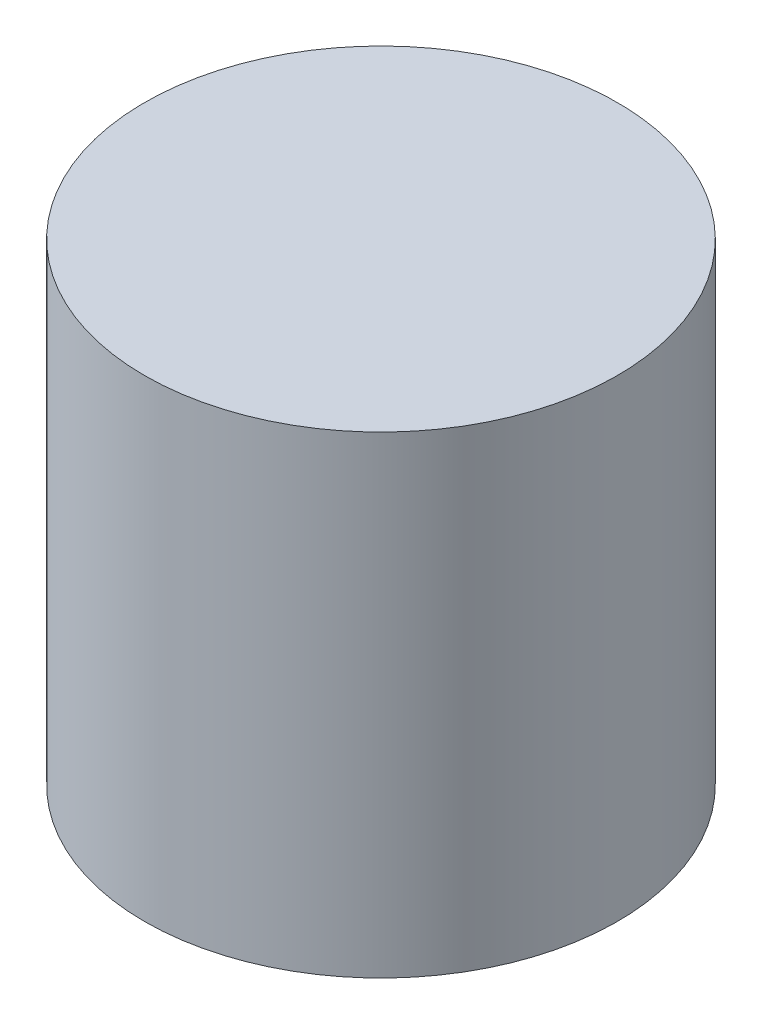
SolidWorks part; units mm, degrees
ref_plane "前视基准面" through (0, 0, 0) normal (0, 0, 1) x (1, 0, 0)
ref_plane "上视基准面" through (0, 0, 0) normal (0, 1, 0) x (1, 0, 0)
ref_plane "右视基准面" through (0, 0, 0) normal (1, 0, 0) x (0, 0, -1)
sketch "草图2" plane through (0, 0, 0) normal (0, 1, 0) x (1, 0, 0)
  circle A0 centre (0, 0) radius 50
  dimension "D1" = 100
extrude "凸台-拉伸1" add sketch "草图2" along normal blind 100
